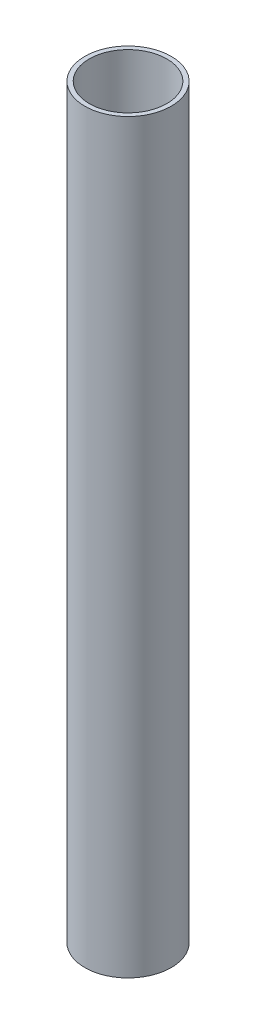
SolidWorks part; units mm, degrees
ref_plane "Front Plane" through (0, 0, 0) normal (0, 0, 1) x (1, 0, 0)
ref_plane "Top Plane" through (0, 0, 0) normal (0, 1, 0) x (1, 0, 0)
ref_plane "Right Plane" through (0, 0, 0) normal (1, 0, 0) x (0, 0, -1)
sketch "Sketch2" plane through (0, 0, 0) normal (0, 1, 0) x (1, 0, 0)
  circle A0 centre (0, 0) radius 12.7
  circle A1 centre (0, 0) radius 11.4
  dimension "D1" = 25.4
  dimension "D2" = 1.3
extrude "Tube" add sketch "Sketch2" along normal blind 219.24
